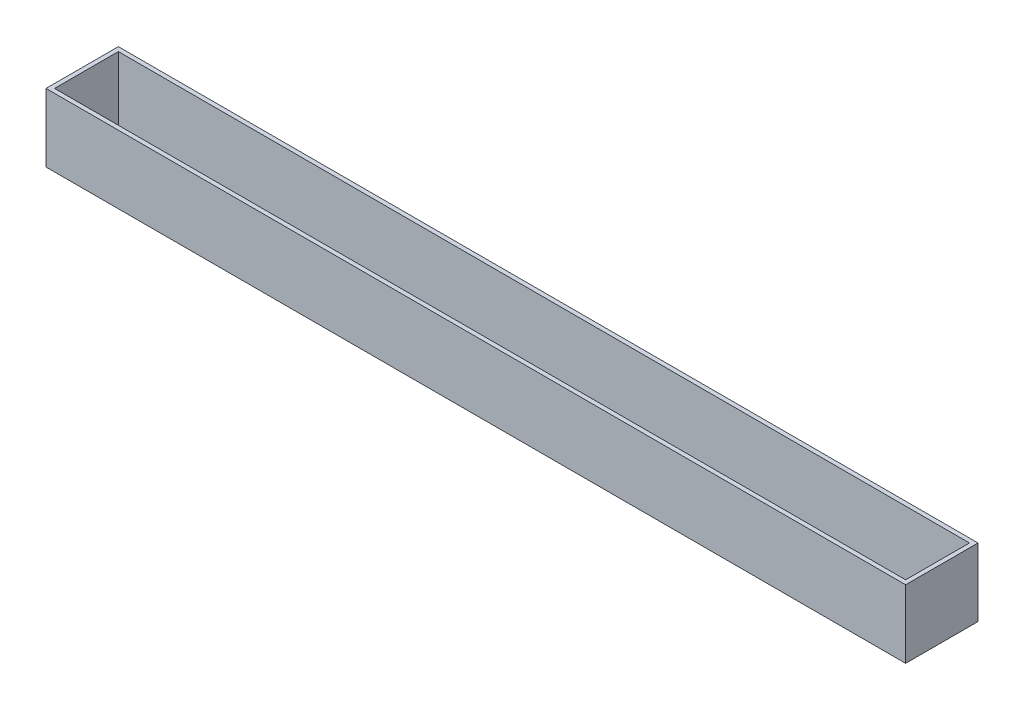
SolidWorks part; units mm, degrees
ref_plane "Front Plane" through (0, 0, 0) normal (0, 0, 1) x (1, 0, 0)
ref_plane "Top Plane" through (0, 0, 0) normal (0, 1, 0) x (1, 0, 0)
ref_plane "Right Plane" through (0, 0, 0) normal (1, 0, 0) x (0, 0, -1)
sketch "Sketch1" plane through (0, 0, 0) normal (0, 1, 0) x (1, 0, 0)
  line L5 (-62.8042, 34) -> (341.1958, 34)
  line L6 (-62.8042, 34) -> (-62.8042, 0)
  line L7 (-62.8042, 0) -> (341.1958, 0)
  line L8 (341.1958, 34) -> (341.1958, 0)
  dimension "D1" = 404
  dimension "D2" = 34
extrude "Boss-Extrude1" add sketch "Sketch1" along normal blind 32
sketch "Sketch2" plane through (0, 32, 0) normal (0, 1, 0) x (1, 0, 0)
  line L5 (-60.8042, 32) -> (339.1958, 32)
  line L6 (-60.8042, 32) -> (-60.8042, 2)
  line L7 (-60.8042, 2) -> (339.1958, 2)
  line L8 (339.1958, 32) -> (339.1958, 2)
  line L9 (-60.8042, 32) -> (339.1958, 2) construction
  line L10 (-60.8042, 2) -> (339.1958, 32) construction
  point P6 (139.1958, 17)
extrude "Cut-Extrude3" cut sketch "Sketch2" against normal blind 30
